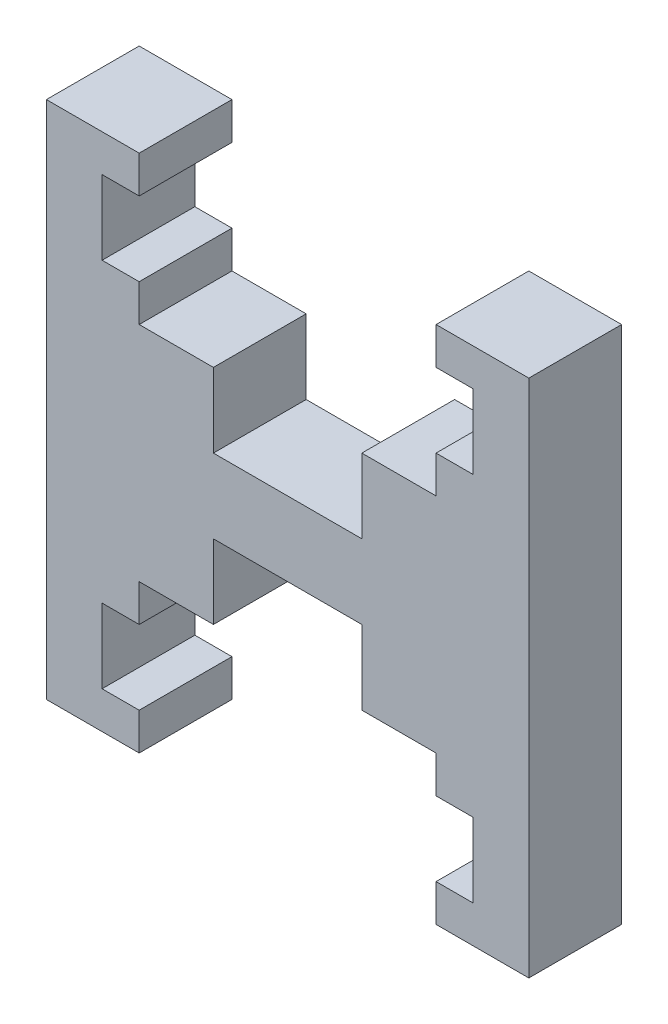
SolidWorks part; units mm, degrees
ref_plane "Front Plane" through (0, 0, 0) normal (0, 0, 1) x (1, 0, 0)
ref_plane "Top Plane" through (0, 0, 0) normal (0, 1, 0) x (1, 0, 0)
ref_plane "Right Plane" through (0, 0, 0) normal (1, 0, 0) x (0, 0, -1)
sketch "Sketch1" plane through (0, 0, 0) normal (0, 0, 1) x (1, 0, 0)
  line L0 (0, 147.0429) -> (0, -133.0036) construction
  line L1 (101.6, -50.8) -> (-101.6, -50.8)
  line L2 (-101.6, -50.8) -> (-101.6, -152.4)
  line L3 (-101.6, -152.4) -> (-203.2, -152.4)
  line L4 (-203.2, -152.4) -> (-203.2, -203.2)
  line L5 (-203.2, -203.2) -> (-254, -203.2)
  line L6 (-254, -203.2) -> (-254, -304.8)
  line L7 (-254, -304.8) -> (-203.2, -304.8)
  line L8 (-203.2, -304.8) -> (-203.2, -355.6)
  line L9 (-203.2, -355.6) -> (-330.2, -355.6)
  line L10 (-330.2, -355.6) -> (-330.2, 355.6)
  line L11 (-407.1074, 0) -> (197.3969, 0) construction
  line L12 (101.6, 50.8) -> (-101.6, 50.8)
  line L13 (-203.2, 355.6) -> (-330.2, 355.6)
  line L14 (-203.2, 304.8) -> (-203.2, 355.6)
  line L15 (-254, 304.8) -> (-203.2, 304.8)
  line L16 (-254, 203.2) -> (-254, 304.8)
  line L17 (-203.2, 203.2) -> (-254, 203.2)
  line L18 (-203.2, 152.4) -> (-203.2, 203.2)
  line L19 (-101.6, 152.4) -> (-203.2, 152.4)
  line L20 (-101.6, 50.8) -> (-101.6, 152.4)
  line L21 (101.6, 50.8) -> (101.6, 152.4)
  line L22 (101.6, 152.4) -> (203.2, 152.4)
  line L23 (203.2, 152.4) -> (203.2, 203.2)
  line L24 (203.2, 203.2) -> (254, 203.2)
  line L25 (254, 203.2) -> (254, 304.8)
  line L26 (254, 304.8) -> (203.2, 304.8)
  line L27 (203.2, 304.8) -> (203.2, 355.6)
  line L28 (203.2, 355.6) -> (330.2, 355.6)
  line L29 (330.2, -355.6) -> (330.2, 355.6)
  line L30 (203.2, -355.6) -> (330.2, -355.6)
  line L31 (203.2, -304.8) -> (203.2, -355.6)
  line L32 (254, -304.8) -> (203.2, -304.8)
  line L33 (254, -203.2) -> (254, -304.8)
  line L34 (203.2, -203.2) -> (254, -203.2)
  line L35 (203.2, -152.4) -> (203.2, -203.2)
  line L36 (101.6, -152.4) -> (203.2, -152.4)
  line L37 (101.6, -50.8) -> (101.6, -152.4)
  point P15 (-330.2, 0)
  point P27 (0, -50.8)
  point P28 (0, 50.8)
  point P44 (330.2, 0)
  dimension "D1" = 101.6
  dimension "D2" = 101.6
  dimension "D3" = 50.8
  dimension "D4" = 127
  dimension "D5" = 355.6
  dimension "D6" = 50.8
  dimension "D7" = 101.6
  dimension "D8" = 50.8
  dimension "D9" = 101.6
extrude "Boss-Extrude1" add sketch "Sketch1" along normal mid plane 127
